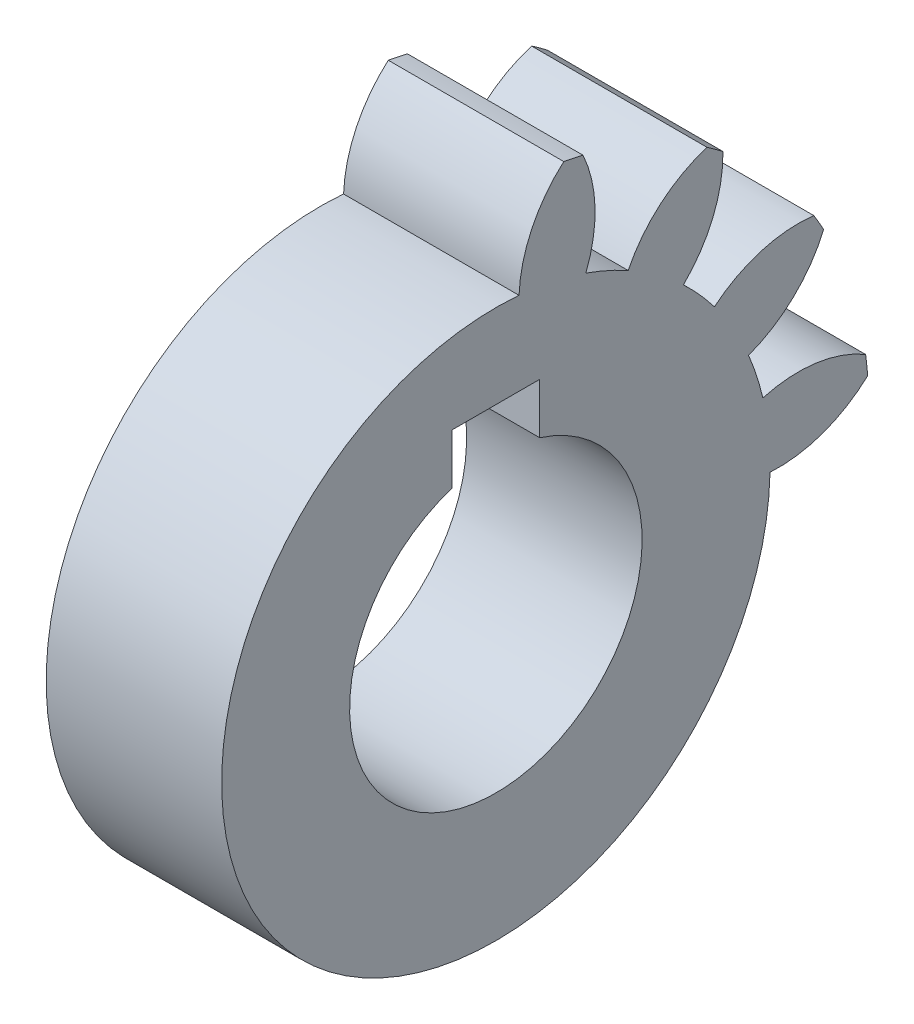
SolidWorks part; units mm, degrees
ref_plane "Plane1" through (0, 0, 0) normal (0, 0, 1) x (1, 0, 0)
ref_plane "Plane2" through (0, 0, 0) normal (0, 1, 0) x (1, 0, 0)
ref_plane "Plane3" through (0, 0, 0) normal (1, 0, 0) x (0, 0, -1)
other "Configuration Table"
sketch "HoldingSke" plane through (0, 0, 0) normal (0, 1, 0) x (1, 0, 0)
  line L0 (0, 0) -> (0.322, -0.0863)
  line L1 (-15, 0) -> (100, 0) construction
  line L2 (0, 0) -> (-2.1039, 2.3779)
  line L3 (0, 0) -> (-11.863, 4.5341)
  line L4 (0, 0) -> (8.3417, 2.2352)
  line L5 (0, 0) -> (-46.8476, -17.4728)
  line L6 (0, 0) -> (-9.9476, -6.7116)
  line L7 (-2.1039, 2.3779) -> (8.6586, 51.2059)
  line L8 (-76.2, 54.61) -> (-73.4, 54.61)
  line L9 (-71.009, 38.7566) -> (-53.1078, 45.2721)
  line L10 (-76.2, 71.12) -> (104.1128, 71.12)
  line L11 (0, 0) -> (-12, 0)
  line L12 (-76.2, 101.6) -> (-76.093, 101.6)
  line L13 (24.9733, 27.94) -> (52.9518, 28.4284)
  line L14 (24.9733, 27.94) -> (24.9743, 27.94)
  line L15 (24.9733, 27.94) -> (100.4006, 29.5858)
  line L16 (-63.627, -3) -> (-12.827, -3)
  circle A0 centre (0, 0) radius 10
  circle A1 centre (0, 0) radius 18.749
  circle A2 centre (0, 0) radius 37.5
  circle A3 centre (0, 0) radius 10
  dimension "MHD" = 37.498
  dimension "Hub_dia" = 75
  dimension "Bore" = 20
  dimension "MBD" = 20
  dimension "Num_teeth" = 15
  dimension "Pitch" = 0.3333
  dimension "Overall_len" = 50
  dimension "Show_teeth" = 15
  dimension "Thickness" = 12
  dimension "OAL" = 50.0001
  dimension "T_dim" = 2.8
  dimension "Ap" = 20
  dimension "H" = 19.05
  dimension "Pitch_radius" = 180.3128
  dimension "Width" = 12
  dimension "Backlash" = 0.107
  dimension "Addendum_fac" = 1
  dimension "Dedendum_fac" = 1.25
  dimension "Clearance_fac" = 0.25
  dimension "Dedendum_add" = 0.001
  dimension "Module" = 3
sketch "BasProSke" plane through (0, 0, 0) normal (0, 1, 0) x (1, 0, 0)
  line L0 (-10, 0) -> (60, 0) construction
  line L1 (0, 0) -> (0, 25.5)
  line L2 (0, 0) -> (12, 0)
  line L3 (12, 0) -> (12, 25.5)
  line L4 (12, 25.5) -> (0, 25.5)
  dimension "Thickness" = 12
  dimension "Diameter" = 51
revolve "Base-Revolve" add sketch "BasProSke" angle 360 about L0
sketch "TooCutSke" plane through (0, 0, 0) normal (1, 0, 0) x (0, 0, -1)
  line L1 (0, 0) -> (0, 107) construction
  line L2 (0, 0) -> (-2.539, 22.3563) construction
  line L3 (0, 0) -> (-9.3126, 43.8125) construction
  line L4 (-2.539, 22.3563) -> (-4.6563, 21.9062) construction
  arc A0 (1.5846, 18.6819) -> (-1.5846, 18.6819) centre (0, 0) ccw
  arc A1 (4.6669, 25.0951) -> (-4.6669, 25.0951) centre (0, 0) ccw
  circle A2 centre (0, 0) radius 22.5 construction
  circle A3 centre (0, 0) radius 21.1431 construction
  arc A4 (-1.5846, 18.6819) -> (-4.6669, 25.0951) centre (-10.5768, 18.3074) ccw
  arc A5 (4.6669, 25.0951) -> (1.5846, 18.6819) centre (10.5768, 18.3074) ccw
  dimension "Root_dia" = 37.498
  dimension "Overcut_dia" = 51.0508
  dimension "Pitch_dia" = 45
  dimension "Base_dia" = 42.2862
  dimension "Flank_rad" = 9
  dimension "Half_ang" = 12
  dimension "Half_CT" = 2.1646
extrude "ToothCut" cut sketch "TooCutSke" along normal through all
fillet "Breaks" [suppressed] radius 0.06
fillet "RootFillets" [suppressed] radius 0.751
pattern_circular "TeethCuts" count 15 every 24 about axis through (-10, 0, 0) along (1, 0, 0) of "ToothCut", "RootFillets", "Breaks"
sketch "HubNeaOneSke" plane through (0, 0, 0) normal (-1, 0, 0) x (0, 0, 1)
  circle A0 centre (0, 0) radius 18.749
  dimension "Diameter" = 37.498
extrude "HubNearOne" [suppressed] add sketch "HubNeaOneSke" along normal blind 38.0001
sketch "HubNeaBotSke" plane through (0, 0, 0) normal (-1, 0, 0) x (0, 0, 1)
  circle A0 centre (0, 0) radius 18.749
  dimension "Diameter" = 37.498
extrude "HubNearBoth" [suppressed] add sketch "HubNeaBotSke" along normal blind 19
ref_plane "FarPln" through (12, 0, 0) normal (1, 0, 0) x (0, 0, -1)
sketch "HubFarSke" plane through (12, 0, 0) normal (1, 0, 0) x (0, 0, -1)
  circle A0 centre (0, 0) radius 18.749
  dimension "Diameter" = 37.498
extrude "HubFar" [suppressed] add sketch "HubFarSke" along normal blind 19
sketch "BorSke" plane through (0, 0, 0) normal (1, 0, 0) x (0, 0, -1)
  circle A0 centre (0, 0) radius 10
  dimension "Diameter" = 20
extrude "Bore" cut sketch "BorSke" along normal mid plane 100.0001
sketch "KeySke" plane through (0, 0, 0) normal (1, 0, 0) x (0, 0, -1)
  line L0 (-3, 0) -> (-3, 12.8)
  line L1 (-3, 12.8) -> (3, 12.8)
  line L2 (3, 12.8) -> (3, 0)
  line L3 (0, 0) -> (0, 34) construction
  line L4 (-3, 0) -> (3, 0)
  dimension "Offset" = 12.8
  dimension "Width" = 6
extrude "Keyway" [suppressed] cut sketch "KeySke" along normal mid plane 100.0001
pattern_circular "Keyway2" [suppressed] count 2 every 90 about axis through (-10, 0, 0) along (1, 0, 0)
sketch "Sketch1" plane through (0, 0, 0) normal (1, 0, 0) x (0, 0, -1)
  line L0 (0, 0) -> (0, 41.6578) construction
  line L1 (0, 18.749) -> (0, 29.2194)
  line L2 (0, 29.2194) -> (-29.8453, 29.2194)
  line L3 (-29.8453, 29.2194) -> (-29.8453, -32.4845)
  line L4 (-29.8453, -32.4845) -> (30.1664, -32.4845)
  line L5 (30.1664, -32.4845) -> (30.1664, -1.6325)
  line L6 (30.1664, -1.6325) -> (18.6778, -1.6325)
  circle A0 centre (0, 0) radius 18.749
  arc A1 (9.0462, 16.4223) -> (6.151, 17.7113) centre (0, 0) ccw construction
extrude "Cut-Extrude1" cut sketch "Sketch1" along normal through all contours A0 L1 L2 L3 L4 L5 L6
sketch "Sketch3" plane through (0, 0, 0) normal (1, 0, 0) x (0, 0, -1)
  line L0 (0, 0) -> (0, 32.9437) construction
  line L2 (-3, 7) -> (3, 7)
  line L3 (-3, 7) -> (-3, 13)
  line L4 (-3, 13) -> (3, 13)
  line L5 (3, 7) -> (3, 13)
  line L6 (-3, 7) -> (3, 13) construction
  line L7 (-3, 13) -> (3, 7) construction
  circle A0 centre (0, 0) radius 10 construction
  point P3 (0, 10)
  dimension "D1" = 6
  dimension "D2" = 6
extrude "Cut-Extrude2" cut sketch "Sketch3" along normal through all both
equation "' \"Module@HoldingSke\" = 6.35"
equation "' \"Num_teeth@HoldingSke\" = 12"
equation "' \"Ap@HoldingSke\" =  20"
equation "' \"Ap@HoldingSke\" = 20"
equation "' \"Width@HoldingSke\" = 0.5 * 25.4"
equation "' \"Hub_dia@HoldingSke\"= 1 * 25.4"
equation "' \"Hub_dia@HoldingSke\" = 1 * 25.4"
equation "' \"Overall_len@HoldingSke\" = 1.0 * 25.4"
equation "' \"Bore@HoldingSke\" = 0.75 * 25.4"
equation "' \"T_dim@HoldingSke\" = 0.1 * 25.4"
equation "' \"Width@KeySke\" = 0.25 * 25.4"
equation "' \"Show_teeth@HoldingSke\" = 13"
equation "' \"Backlash@HoldingSke\" = 0.009 * 25.4"
equation "' \"Addendum_fac@HoldingSke\" = 1.0"
equation "' \"Dedendum_fac@HoldingSke\" = 1.25"
equation "' \"Dedendum_add@HoldingSke\" = 0.00005 * 25.4"
equation "' \"Clearance_fac@HoldingSke\" = 0.25"
equation "\"Pitch@HoldingSke\" = 1 / \"Module@HoldingSke\""
equation "\"Overcut_dia@TooCutSke\" = (\"Num_teeth@HoldingSke\" + 2 * \"Addendum_fac@HoldingSke\") / \"Pitch@HoldingSke\" + 0.002 * 25.4"
equation "\"Pitch_dia@TooCutSke\" = \"Num_teeth@HoldingSke\" / \"Pitch@HoldingSke\""
equation "\"Base_dia@TooCutSke\" = \"Num_teeth@HoldingSke\" / \"Pitch@HoldingSke\" * cos((\"Ap@HoldingSke\"  * 3.14159265 / 180))"
equation "\"Root_dia@TooCutSke\" = (\"Num_teeth@HoldingSke\" + 2) / \"Pitch@HoldingSke\" - 2 * (\"Addendum_fac@HoldingSke\" + \"Dedendum_fac@HoldingSke\") / \"Pitch@HoldingSke\" - \"Dedendum_add@HoldingSke\" * 2"
equation "\"Half_ang@TooCutSke\" = 180 / \"Num_teeth@HoldingSke\""
equation "\"Half_CT@TooCutSke\" = \"Num_teeth@HoldingSke\" / \"Pitch@HoldingSke\" * sin((3.14159265 / 2 / \"Num_teeth@HoldingSke\")) / 2 - 7 * \"Backlash@HoldingSke\" / 4"
equation "\"Flank_rad@TooCutSke\" = \"Num_teeth@HoldingSke\" / \"Pitch@HoldingSke\" / 5"
equation "\"Radius@RootFillets\" = \"Clearance_fac@HoldingSke\" / \"Pitch@HoldingSke\" + \"Dedendum_add@HoldingSke\""
equation "\"Break_rad@Breaks\" = 0.02 / \"Pitch@HoldingSke\""
equation "\"Thickness@HoldingSke\" = \"Width@HoldingSke\""
equation "\"OAL@HoldingSke\" = \"Thickness@HoldingSke\""
equation "\"MHD@HoldingSke\" = (\"Num_teeth@HoldingSke\" + 2) / \"Pitch@HoldingSke\" - 2 * (\"Addendum_fac@HoldingSke\" + \"Dedendum_fac@HoldingSke\")  / \"Pitch@HoldingSke\" - \"Dedendum_add@HoldingSke\" * 2"
equation "\"MBD@HoldingSke\" = (\"Num_teeth@HoldingSke\" + 2) / \"Pitch@HoldingSke\" - 2 * (\"Addendum_fac@HoldingSke\" + \"Dedendum_fac@HoldingSke\")  / \"Pitch@HoldingSke\" - \"Dedendum_add@HoldingSke\" * 2 - 0.002 * 25.4"
equation "\"MHD@HoldingSke\" = ((sgn( \"MHD@HoldingSke\" - \"Hub_dia@HoldingSke\" )-1)*( \"MHD@HoldingSke\" - \"Hub_dia@HoldingSke\" ))/-2+ \"Hub_dia@HoldingSke\""
equation "\"MBD@HoldingSke\" = ((sgn( \"MBD@HoldingSke\" - \"Bore@HoldingSke\" )-1)*( \"MBD@HoldingSke\" - \"Bore@HoldingSke\" ))/-2+ \"Bore@HoldingSke\""
equation "\"OAL@HoldingSke\" = ((sgn( \"OAL@HoldingSke\" - \"Overall_len@HoldingSke\" )+1)*( \"OAL@HoldingSke\" - \"Overall_len@HoldingSke\" ))/2 + \"Overall_len@HoldingSke\" + 0.000002 * 25.4"
equation "\"Num_teeth@TeethCuts\" = int( \"Show_teeth@HoldingSke\" ) + 1"
equation "\"Num_teeth@TeethCuts\" = ((sgn( \"Num_teeth@TeethCuts\" - \"Num_teeth@HoldingSke\" )-1)*( \"Num_teeth@TeethCuts\" - \"Num_teeth@HoldingSke\" ))/-2+ \"Num_teeth@HoldingSke\""
equation "\"Num_teeth@TeethCuts\" = ((sgn( \"Num_teeth@TeethCuts\" - 2.0)+1)*( \"Num_teeth@TeethCuts\" - 2.0))/2 +2.0"
equation "\"Angle@TeethCuts\" = 360.0 / \"Num_teeth@HoldingSke\""
equation "\"Diameter@BasProSke\" = (\"Num_teeth@HoldingSke\" + 2 * \"Addendum_fac@HoldingSke\") / \"Pitch@HoldingSke\""
equation "\"Thickness@BasProSke\"  = \"Thickness@HoldingSke\""
equation "' \"Fillet_rad@BasProSke\" =  \"Thickness@HoldingSke\" * 0.05"
equation "' \"Fillet_rad@BasProSke\" = \"Thickness@HoldingSke\" * 0.05"
equation "\"MHD@HoldingSke\" = ((sgn( \"MHD@HoldingSke\" - \"Root_dia@TooCutSke\" )-1)*( \"MHD@HoldingSke\" - \"Root_dia@TooCutSke\" ))/-2+ \"Root_dia@TooCutSke\""
equation "\"Diameter@HubNeaOneSke\" = \"MHD@HoldingSke\""
equation "\"Length@HubNearOne\" = \"OAL@HoldingSke\" - \"Thickness@BasProSke\""
equation "\"Diameter@HubNeaBotSke\" = \"MHD@HoldingSke\""
equation "\"Length@HubNearBoth\" = ( \"OAL@HoldingSke\" - \"Thickness@BasProSke\" ) / 2.0"
equation "\"Thickness@FarPln\" = \"Thickness@BasProSke\""
equation "\"Diameter@HubFarSke\" = \"MHD@HoldingSke\""
equation "\"Length@HubFar\" = ( \"OAL@HoldingSke\" - \"Thickness@BasProSke\" ) / 2.0"
equation "\"Diameter@BorSke\" = \"MBD@HoldingSke\""
equation "\"D1@Bore\" = \"OAL@HoldingSke\" * 2.0"
equation "\"D1@Keyway\" = \"OAL@HoldingSke\" * 2.0"
equation "\"Offset@KeySke\" = \"T_dim@HoldingSke\" + \"MBD@HoldingSke\" / 2.0"
